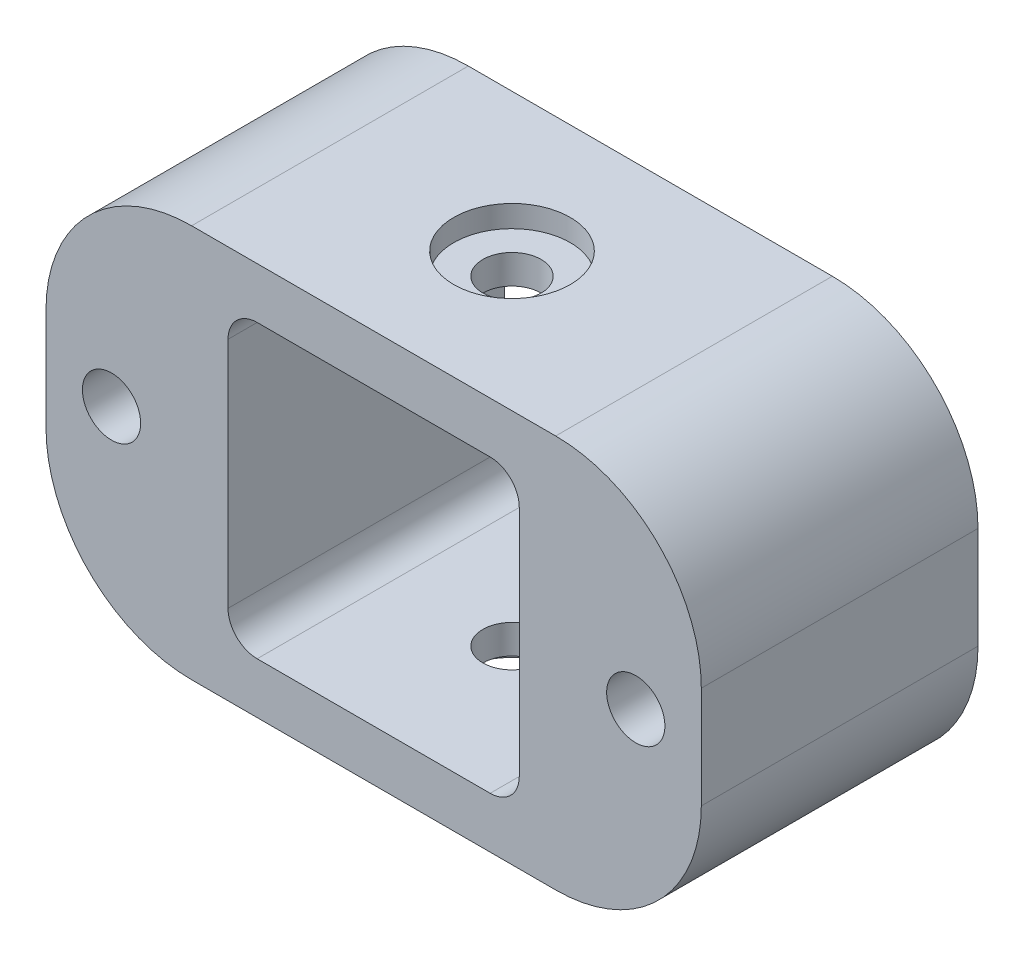
SolidWorks part; units mm, degrees
ref_plane "Front Plane" through (0, 0, 0) normal (0, 0, 1) x (1, 0, 0)
ref_plane "Top Plane" through (0, 0, 0) normal (0, 1, 0) x (1, 0, 0)
ref_plane "Right Plane" through (0, 0, 0) normal (1, 0, 0) x (0, 0, -1)
sketch "Sketch1" plane through (0, 0, 0) normal (0, 0, 1) x (1, 0, 0)
  line L0 (-8, -10) -> (8, -10)
  line L1 (-10, -8) -> (-10, 8)
  line L2 (-8, 10) -> (8, 10)
  line L3 (10, -8) -> (10, 8)
  line L4 (-10, -10) -> (10, 10) construction
  line L5 (-10, 10) -> (10, -10) construction
  line L7 (-12.5, -13.5) -> (12.5, -13.5)
  line L8 (-22.5, -3.5) -> (-22.5, 3.5)
  line L9 (-12.5, 13.5) -> (12.5, 13.5)
  line L10 (22.5, -3.5) -> (22.5, 3.5)
  line L11 (-22.5, -13.5) -> (22.5, 13.5) construction
  line L12 (-22.5, 13.5) -> (22.5, -13.5) construction
  arc A0 (-10, -8) -> (-8, -10) centre (-8, -8) ccw
  arc A1 (8, -10) -> (10, -8) centre (8, -8) ccw
  arc A2 (10, 8) -> (8, 10) centre (8, 8) ccw
  arc A3 (-8, 10) -> (-10, 8) centre (-8, 8) ccw
  circle A4 centre (-18, 0) radius 2
  circle A5 centre (18, 0) radius 2
  arc A6 (12.5, 13.5) -> (22.5, 3.5) centre (12.5, 3.5) cw
  arc A7 (22.5, -3.5) -> (12.5, -13.5) centre (12.5, -3.5) cw
  arc A8 (-12.5, -13.5) -> (-22.5, -3.5) centre (-12.5, -3.5) cw
  arc A9 (-22.5, 3.5) -> (-12.5, 13.5) centre (-12.5, 3.5) cw
  point P0 (0, 0)
  point P21 (0, 0)
  dimension "D2" = 2
  dimension "D3" = 18
  dimension "D7" = 10
  dimension "D1" = 20
  dimension "D4" = 18
  dimension "D5" = 45
  dimension "D6" = 27
extrude "Boss-Extrude1" add sketch "Sketch1" along normal blind 19
sketch "Sketch3" plane through (0, 13.5, 0) normal (0, 1, 0) x (1, 0, 0)
  line L0 (12.5, -9.5) -> (-12.5, -9.5) construction
  line L1 (12.5, -19) -> (12.5, 0) construction
  line L2 (-12.5, -19) -> (-12.5, 0) construction
  circle A0 centre (0, -9.5) radius 2
extrude "Cut-Extrude2" cut sketch "Sketch3" against normal through all
sketch "Sketch4" plane through (0, 13.5, 0) normal (0, 1, 0) x (1, 0, 0)
  circle A0 centre (0, -9.5) radius 4
extrude "Cut-Extrude3" cut sketch "Sketch4" against normal blind 1.5
sketch "Sketch5" plane through (0, -13.5, 0) normal (0, -1, 0) x (1, 0, 0)
  circle A0 centre (0, 9.5) radius 4
extrude "Cut-Extrude4" cut sketch "Sketch5" against normal blind 1.5
